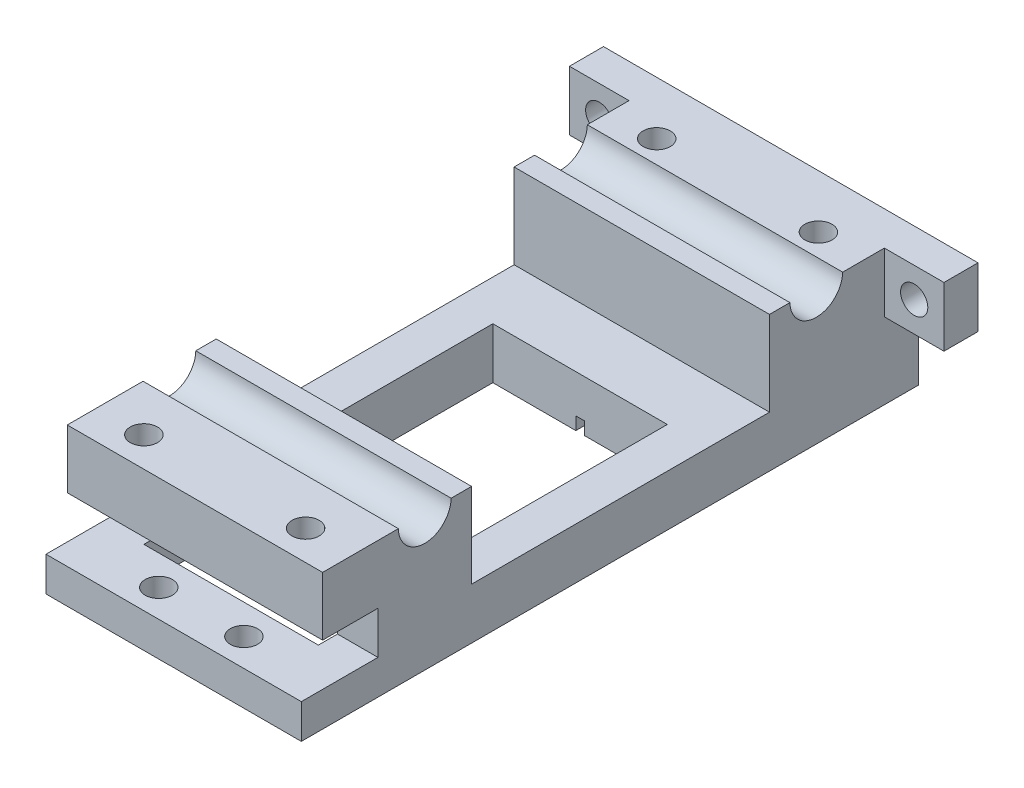
SolidWorks part; units mm, degrees
ref_plane "Front Plane" through (0, 0, 0) normal (0, 0, 1) x (1, 0, 0)
ref_plane "Top Plane" through (0, 0, 0) normal (0, 1, 0) x (1, 0, 0)
ref_plane "Right Plane" through (0, 0, 0) normal (1, 0, 0) x (0, 0, -1)
sketch "Sketch3" plane through (0, 0, 0) normal (0, 1, 0) x (1, 0, 0)
  line L1 (-15, 36.25) -> (15, 36.25)
  line L2 (-15, 36.25) -> (-15, -36.25)
  line L3 (-15, -36.25) -> (15, -36.25)
  line L4 (15, 36.25) -> (15, -36.25)
  line L5 (-15, 36.25) -> (15, -36.25) construction
  line L6 (-15, -36.25) -> (15, 36.25) construction
  point P0 (0, 0)
  dimension "D1" = 72.5
  dimension "D2" = 30
extrude "Boss-Extrude2" add sketch "Sketch3" along normal blind 15.95
sketch "Sketch7" plane through (0, 0, 0) normal (0, -1, 0) x (1, 0, 0)
  line L1 (10.25, -11.5) -> (-10.25, -11.5)
  line L2 (10.25, -11.5) -> (10.25, 29.5)
  line L3 (10.25, 29.5) -> (-10.25, 29.5)
  line L4 (-10.25, -11.5) -> (-10.25, 29.5)
  line L5 (10.25, -11.5) -> (-10.25, 29.5) construction
  line L6 (10.25, 29.5) -> (-10.25, -11.5) construction
  line L7 (-15, 36.25) -> (15, 36.25) construction
  point P0 (0, 9)
  dimension "D1" = 9
  dimension "D2" = 41
  dimension "D3" = 20.5
  dimension "D4" = 6.75
extrude "Cut-Extrude5" cut sketch "Sketch7" against normal blind 8.1
sketch "Sketch8" plane through (0, 15.95, 0) normal (0, 1, 0) x (1, 0, 0)
  line L0 (15, -36.25) -> (15, 36.25) construction
  line L1 (-15, 18.75) -> (15, 18.75)
  line L2 (-15, 18.75) -> (-15, -16.25)
  line L3 (-15, -16.25) -> (15, -16.25)
  line L4 (15, 18.75) -> (15, -16.25)
  line L5 (-15, 18.75) -> (15, -16.25) construction
  line L6 (-15, -16.25) -> (15, 18.75) construction
  line L7 (-15, -36.25) -> (15, -36.25) construction
  point P0 (0, 1.25)
  dimension "D1" = 35
  dimension "D2" = 20
extrude "Cut-Extrude6" cut sketch "Sketch8" against normal blind 9.95
sketch "Sketch9" plane through (15, 0, 0) normal (1, 0, 0) x (0, 0, -1)
  line L0 (-36.25, 15.95) -> (-33.75, 15.95)
  line L1 (-36.25, 15.95) -> (-16.25, 15.95) construction
  line L2 (-33.75, 15.95) -> (-33.75, 9.05)
  line L3 (-33.75, 9.05) -> (-27.25, 9.05)
  line L4 (-27.25, 9.05) -> (-27.25, 4.05)
  line L5 (-27.25, 4.05) -> (-36.25, 4.05)
  line L6 (-36.25, 15.95) -> (-36.25, 0) construction
  line L7 (-36.25, 4.05) -> (-36.25, 15.95)
  line L9 (-36.25, 0) -> (36.25, 0) construction
  dimension "D1" = 2.5
  dimension "D2" = 4.05
  dimension "D3" = 5
  dimension "D4" = 9
extrude "Cut-Extrude7" cut sketch "Sketch9" against normal through all
sketch "Sketch10" plane through (15, 0, 0) normal (1, 0, 0) x (0, 0, -1)
  line L0 (18.75, 15.95) -> (36.25, 15.95) construction
  line L1 (36.25, 15.95) -> (36.25, 0) construction
  circle A0 centre (24.25, 16) radius 3.1
  circle A1 centre (-21.75, 16) radius 3.1
  dimension "D1" = 6.2
  dimension "D2" = 6.2
  dimension "D4" = 12
  dimension "D5" = 46
  dimension "D3" = 0.05
extrude "Cut-Extrude8" cut sketch "Sketch10" against normal through all
sketch "Sketch11" plane through (0, 15.95, 0) normal (0, 1, 0) x (1, 0, 0)
  line L0 (15, -33.75) -> (15, -24.8496) construction
  line L1 (-15, -24.8496) -> (-15, -33.75) construction
  line L2 (-15, -33.75) -> (15, -33.75) construction
  line L3 (15, 36.25) -> (-15, 36.25) construction
  circle A0 centre (-9.5, -30.25) radius 1.6
  circle A1 centre (9.5, -30.25) radius 1.6
  circle A2 centre (-9.5, 30) radius 1.6
  circle A3 centre (9.5, 30) radius 1.6
  dimension "D1" = 3.2
  dimension "D2" = 3.2
  dimension "D3" = 5.5
  dimension "D4" = 5.5
  dimension "D5" = 3.5
  dimension "D6" = 3.2
  dimension "D7" = 3.2
  dimension "D8" = 6.25
extrude "Cut-Extrude9" cut sketch "Sketch11" against normal up to next
sketch "Sketch12" plane through (0, 4.05, 0) normal (0, 1, 0) x (1, 0, 0)
  line L1 (-10.25, -29.5) -> (10.25, -29.5) construction
  line L2 (-10.25, 11.5) -> (10.25, 11.5) construction
  circle A0 centre (-5, -33) radius 1.6
  circle A1 centre (5, -33) radius 1.6
  circle A2 centre (-5, 15) radius 1.6
  circle A3 centre (5, 15) radius 1.6
  dimension "D1" = 3.2
  dimension "D2" = 3.2
  dimension "D5" = 5
  dimension "D6" = 3.2
  dimension "D7" = 3.2
  dimension "D3" = 3.5
  dimension "D4" = 3.5
  dimension "D8" = 10
extrude "Cut-Extrude10" cut sketch "Sketch12" against normal up to next
sketch "Sketch13" plane through (0, 0, -36.25) normal (0, 0, -1) x (-1, 0, 0)
  line L1 (15, 15.95) -> (22, 15.95)
  line L2 (15, 15.95) -> (15, 8.95)
  line L3 (15, 8.95) -> (22, 8.95)
  line L4 (22, 15.95) -> (22, 8.95)
  line L5 (-15, 15.95) -> (-22, 15.95)
  line L6 (-15, 15.95) -> (-15, 8.95)
  line L7 (-15, 8.95) -> (-22, 8.95)
  line L8 (-22, 15.95) -> (-22, 8.95)
  circle A0 centre (18.5, 12.45) radius 1.6
  circle A1 centre (-18.5, 12.45) radius 1.6
  dimension "D3" = 3.2
  dimension "D4" = 3.5
  dimension "D5" = 3.5
  dimension "D8" = 3.2
  dimension "D9" = 3.5
  dimension "D10" = 3.5
  dimension "D1" = 7
  dimension "D2" = 7
  dimension "D6" = 7
  dimension "D7" = 7
extrude "Boss-Extrude3" add sketch "Sketch13" against normal blind 4
sketch "Sketch14" plane through (0, 0, 0) normal (1, 0, 0) x (0, 0, -1)
  line L0 (18.3, 0) -> (11.5, 0)
  line L5 (-36.3, 0) -> (-29.5, 1.5)
  line L6 (-36.3, 1.5) -> (-29.5, 1.5) construction
  line L7 (-36.3, 1.5) -> (-36.3, 0) construction
  line L9 (-9, 0) -> (-9, -5.8853) construction
  line L10 (-36.3, 0) -> (-29.5, 0)
  line L11 (-29.5, 1.5) -> (-29.5, 0)
  line L12 (-36.3, 1.5) -> (-29.5, 0) construction
  line L13 (-36.3, 0) -> (-29.5, 1.5) construction
  line L14 (-36.3, 0) -> (-36.3, -2.4) construction
  line L18 (-36.3, 0) -> (-36.3, -2.4) construction
  line L19 (18.3, 0) -> (11.5, 1.5)
  line L20 (11.5, 1.5) -> (11.5, 0)
  point P0 (-32.9, 0.75)
  dimension "D1" = 1.5
  dimension "D2" = 6.8
  dimension "D3" = 9
extrude "Cut-Extrude11" cut sketch "Sketch14" against normal mid plane 1
